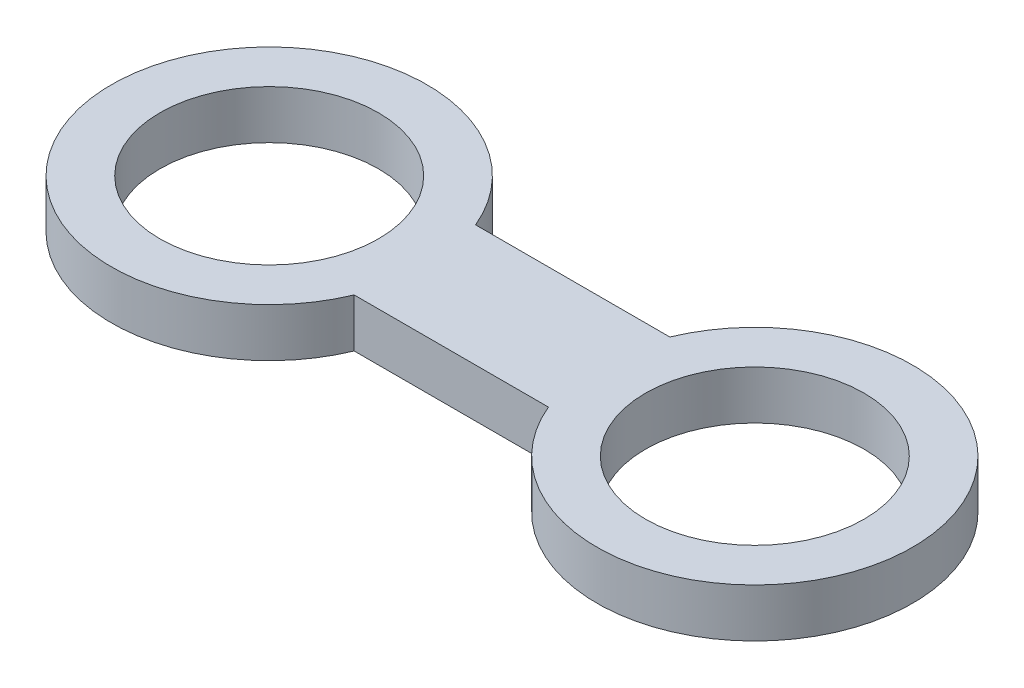
SolidWorks part; units mm, degrees
ref_plane "Plano frontal" through (0, 0, 0) normal (0, 0, 1) x (1, 0, 0)
ref_plane "Plano superior" through (0, 0, 0) normal (0, 1, 0) x (1, 0, 0)
ref_plane "Plano direito" through (0, 0, 0) normal (1, 0, 0) x (0, 0, -1)
sketch "Esboço1" plane through (0, 0, 0) normal (0, 1, 0) x (1, 0, 0)
  line L0 (0, 0) -> (20, 0) construction
  line L1 (6, -2.5) -> (14, -2.5)
  line L2 (6, 2.5) -> (14, 2.5)
  line L3 (14, 2.5) -> (20, 2.5) construction
  line L4 (0, 2.5) -> (20, 2.5) construction
  line L5 (14, -2.5) -> (20, -2.5) construction
  line L6 (0, -2.5) -> (20, -2.5) construction
  line L7 (0, 2.5) -> (6, 2.5) construction
  line L8 (0, -2.5) -> (6, -2.5) construction
  arc A0 (6, 2.5) -> (6, -2.5) centre (0, 0) ccw
  arc A1 (14, -2.5) -> (14, 2.5) centre (20, 0) ccw
  arc A2 (6.5, 0) -> (6, 2.5) centre (0, 0) ccw construction
  arc A3 (14, 2.5) -> (13.5, 0) centre (20, 0) ccw construction
  arc A4 (13.5, 0) -> (14, -2.5) centre (20, 0) ccw construction
  arc A5 (6, -2.5) -> (6.5, 0) centre (0, 0) ccw construction
  dimension "D1" = 13
  dimension "D2" = 20
  dimension "D3" = 2.5
  dimension "D4" = 2.5
extrude "Ressalto-extrusão1" add sketch "Esboço1" against normal blind 2
sketch "Esboço2" plane through (0, 0, 0) normal (0, 1, 0) x (1, 0, 0)
  line L0 (0, 0) -> (20, 0) construction
  circle A0 centre (0, 0) radius 4.5
  circle A1 centre (20, 0) radius 4.5
  dimension "D1" = 9
extrude "Corte-extrusão1" cut sketch "Esboço2" against normal blind 2
